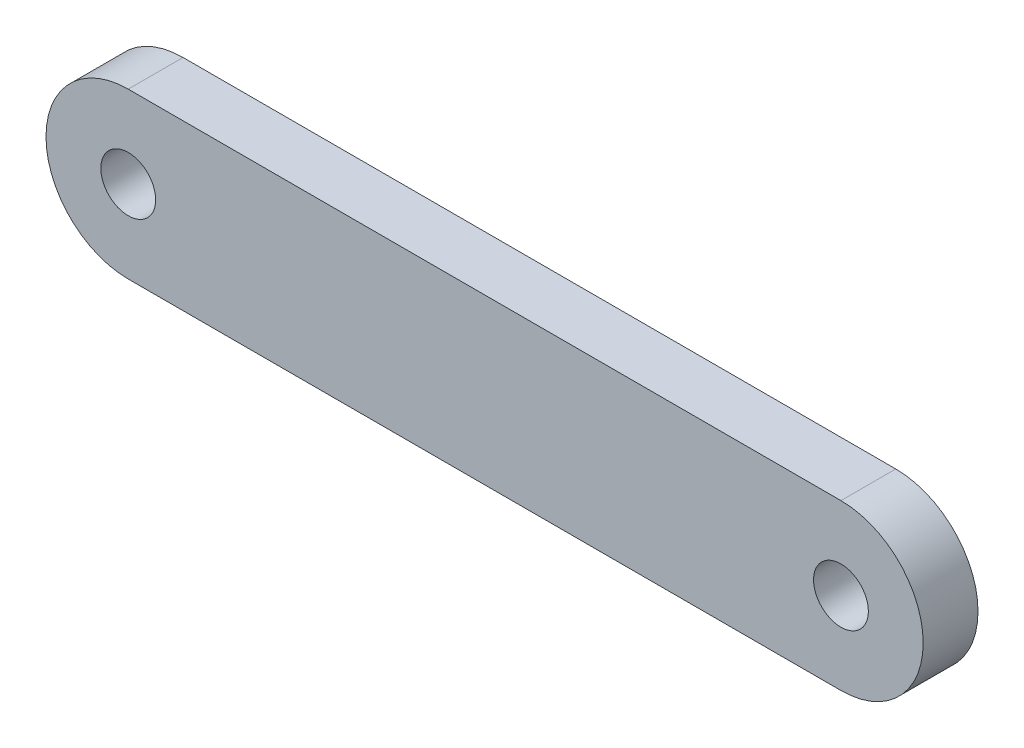
SolidWorks part; units mm, degrees
ref_plane "Front Plane" through (0, 0, 0) normal (0, 0, 1) x (1, 0, 0)
ref_plane "Top Plane" through (0, 0, 0) normal (0, 1, 0) x (1, 0, 0)
ref_plane "Right Plane" through (0, 0, 0) normal (1, 0, 0) x (0, 0, -1)
sketch "Sketch1" plane through (0, 0, 0) normal (0, 0, 1) x (1, 0, 0)
  line L0 (-65, 0) -> (65, 0) construction
  line L1 (-65, 15) -> (65, 15)
  line L2 (-65, -15) -> (65, -15)
  arc A0 (-65, 15) -> (-65, -15) centre (-65, 0) ccw
  arc A1 (65, -15) -> (65, 15) centre (65, 0) ccw
  circle A2 centre (-65, 0) radius 5
  circle A3 centre (65, 0) radius 5
  point P2 (0, 0)
  point P12 (0, -15)
  dimension "D1" = 10
  dimension "D2" = 10
  dimension "D3" = 130
  dimension "D4" = 30
extrude "Boss-Extrude1" add sketch "Sketch1" along normal blind 10
